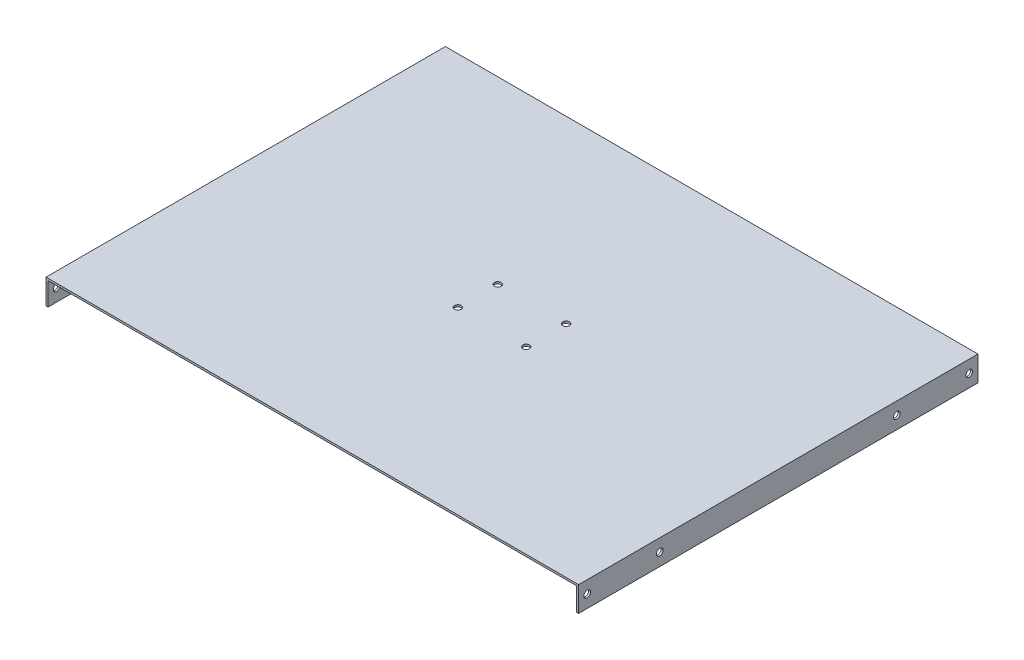
SolidWorks part; units mm, degrees
ref_plane "Plano frontal" through (0, 0, 0) normal (0, 0, 1) x (1, 0, 0)
ref_plane "Plano superior" through (0, 0, 0) normal (0, 1, 0) x (1, 0, 0)
ref_plane "Plano direito" through (0, 0, 0) normal (1, 0, 0) x (0, 0, -1)
sketch "Esboço1" plane through (0, 0, 0) normal (0, 1, 0) x (1, 0, 0)
  line L1 (-160, -120) -> (160, -120)
  line L2 (-160, -120) -> (-160, 120)
  line L3 (-160, 120) -> (160, 120)
  line L4 (160, -120) -> (160, 120)
  line L5 (-160, -120) -> (160, 120) construction
  line L6 (-160, 120) -> (160, -120) construction
  point P0 (0, 0)
  dimension "D1" = 320
  dimension "D2" = 240
extrude "Ressalto-extrusão1" add sketch "Esboço1" along normal blind 15
sketch "Esboço2" plane through (0, 0, 0) normal (0, 1, 0) x (1, 0, 0)
  line L0 (160, 120) -> (-160, 120) construction
  line L1 (-158.8, -120) -> (158.8, -120)
  line L2 (-158.8, -120) -> (-158.8, 120)
  line L3 (-158.8, 120) -> (158.8, 120)
  line L4 (158.8, -120) -> (158.8, 120)
  line L5 (-158.8, -120) -> (158.8, 120) construction
  line L6 (-158.8, 120) -> (158.8, -120) construction
  point P0 (0, 0)
  dimension "D1" = 317.6
extrude "Corte-extrusão1" cut sketch "Esboço2" along normal blind 13.8
sketch "Esboço3" plane through (0, 0, 0) normal (0, 1, 0) x (1, 0, 0)
  line L0 (-160, 120) -> (-160, -120) construction
  line L1 (-160, -120) -> (160, -120) construction
  line L2 (0, 0) -> (-187.3625, 0) construction
  line L3 (-187.3625, 0) -> (0, 0) construction
  line L4 (0, 0) -> (0, -129.0808) construction
  circle A0 centre (-20.52, -12) radius 2
  circle A1 centre (20.52, -12) radius 2
  circle A2 centre (20.52, 12) radius 2
  circle A3 centre (-20.52, 12) radius 2
  dimension "D3" = 4
  dimension "D1" = 139.48
  dimension "D2" = 108
extrude "Corte-extrusão2" cut sketch "Esboço3" along normal blind 13.8 from offset 10 contours A3 | A2 | A1 | A0
sketch "Esboço4" plane through (0, 0, 0) normal (1, 0, 0) x (0, 0, -1)
  line L0 (120, 15) -> (120, 0) construction
  line L1 (0, 31.5048) -> (0, -18.2642) construction
  circle A0 centre (114.8, 7.5) radius 2
  circle A1 centre (71.2, 7.5) radius 2
  circle A2 centre (-114.8, 7.5) radius 2
  circle A3 centre (-71.2, 7.5) radius 2
  dimension "D3" = 4
  dimension "D4" = 4
  dimension "D1" = 5.2
  dimension "D2" = 43.6
extrude "Corte-extrusão3" cut sketch "Esboço4" against normal blind 170 and the other way blind 170
